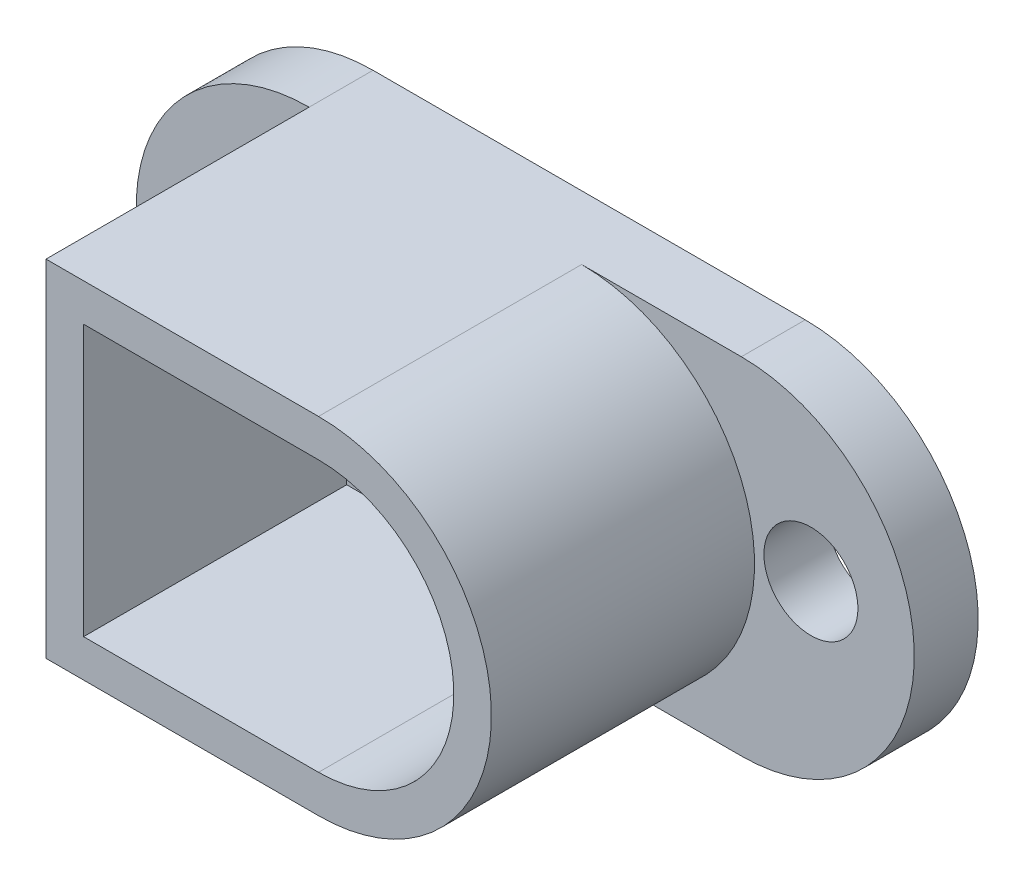
SolidWorks part; units mm, degrees
ref_plane "Plan de face" through (0, 0, 0) normal (0, 0, 1) x (1, 0, 0)
ref_plane "Plan de dessus" through (0, 0, 0) normal (0, 1, 0) x (1, 0, 0)
ref_plane "Plan de droite" through (0, 0, 0) normal (1, 0, 0) x (0, 0, -1)
sketch "Esquisse1" plane through (0, 0, 0) normal (0, 0, 1) x (1, 0, 0)
  line L0 (-7.25, -4.6) -> (-7.25, 4.6)
  line L1 (-7.25, 4.6) -> (0, 4.6)
  line L2 (-7.25, -4.6) -> (0, -4.6)
  line L3 (-6.25, -3.6) -> (-6.25, 3.6)
  line L4 (-6.25, 3.6) -> (0, 3.6)
  line L5 (-6.25, -3.6) -> (0, -3.6)
  arc A0 (0, 4.6) -> (0, -4.6) centre (0, 0) cw
  arc A1 (0, 3.6) -> (0, -3.6) centre (0, 0) cw
  dimension "D2" = 4.6
  dimension "D1" = 9.2
  dimension "D3" = 7.25
  dimension "D4" = 1
extrude "Boss.-Extru.1" add sketch "Esquisse1" along normal blind 7
sketch "Esquisse2" plane through (0, 0, 0) normal (0, 0, -1) x (-1, 0, 0)
  line L0 (7.25, 4.6) -> (-4.25, 4.6)
  line L1 (-4.25, -4.6) -> (7.25, -4.6)
  line L2 (0, 4.6) -> (7.25, 4.6) construction
  line L3 (7.25, -4.6) -> (0, -4.6) construction
  line L4 (7.25, 4.6) -> (7.25, -4.6) construction
  arc A0 (-4.25, 4.6) -> (-4.25, -4.6) centre (-4.25, 0) ccw
  arc A1 (7.25, 4.6) -> (7.25, -4.6) centre (7.25, 0) cw
  circle A2 centre (9.1, 0.35) radius 1.25
  circle A3 centre (-6.1, 0.35) radius 1.25
  dimension "D1" = 2.5
  dimension "D2" = 2.5
  dimension "D6" = 11.5
  dimension "D3" = 4.25
  dimension "D4" = 4.25
  dimension "D5" = 15.2
  dimension "D7" = 1.85
  dimension "D8" = 1.8828
extrude "Boss.-Extru.2" add sketch "Esquisse2" along normal blind 1.7
